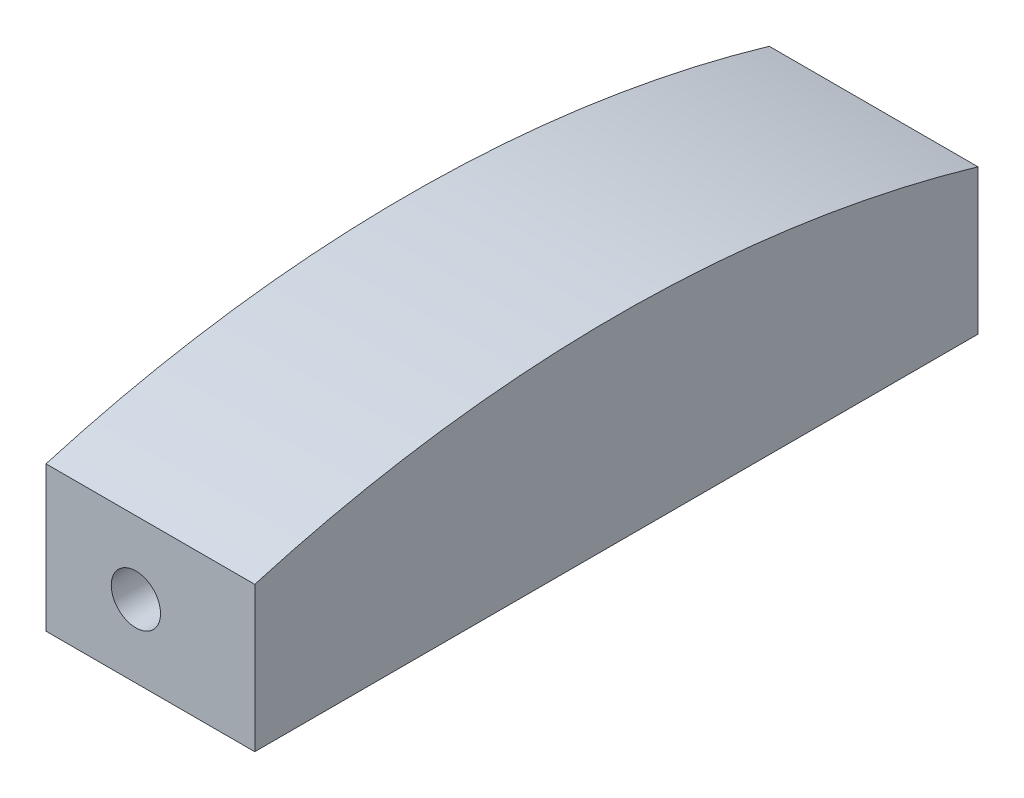
SolidWorks part; units mm, degrees
ref_plane "Front Plane" through (0, 0, 0) normal (0, 0, 1) x (1, 0, 0)
ref_plane "Top Plane" through (0, 0, 0) normal (0, 1, 0) x (1, 0, 0)
ref_plane "Right Plane" through (0, 0, 0) normal (1, 0, 0) x (0, 0, -1)
sketch "Sketch1" plane through (0, 0, 0) normal (0, 1, 0) x (1, 0, 0)
  line L1 (0, 0) -> (18.288, 0)
  line L2 (0, 0) -> (0, 63.357)
  line L3 (0, 63.357) -> (18.288, 63.357)
  line L4 (18.288, 0) -> (18.288, 63.357)
  line L5 (2.794, 58.277) -> (12.954, 58.277)
  line L6 (2.794, 58.277) -> (2.794, 53.197)
  line L7 (2.794, 53.197) -> (12.954, 53.197)
  line L8 (12.954, 58.277) -> (12.954, 53.197)
  line L9 (2.794, 10.16) -> (12.954, 10.16)
  line L10 (2.794, 10.16) -> (2.794, 5.08)
  line L11 (2.794, 5.08) -> (12.954, 5.08)
  line L12 (12.954, 10.16) -> (12.954, 5.08)
  dimension "D1" = 18.288
  dimension "D2" = 5.08
  dimension "D3" = 10.16
  dimension "D4" = 5.08
  dimension "D5" = 5.08
  dimension "D6" = 2.794
  dimension "D7" = 5.08
  dimension "D9" = 43.037
extrude "Boss-Extrude1" add sketch "Sketch1" along normal blind 12.7
sketch "Sketch2" plane through (18.288, 0, 0) normal (1, 0, 0) x (0, 0, -1)
  line L0 (0, 12.7) -> (63.357, 12.7)
  arc A0 (0, 12.7) -> (63.357, 12.7) centre (31.6785, -95.6141) cw
extrude "Boss-Extrude2" add sketch "Sketch2" against normal up to surface (18.288 mm away) up to face at (0, 6.35, -31.6785)
sketch "Sketch6" plane through (0, 0, 0) normal (0, 0, 1) x (1, 0, 0)
  line L0 (0, 0) -> (18.288, 0) construction
  line L1 (0, 12.7) -> (18.288, 12.7) construction
  circle A0 centre (7.874, 6.35) radius 2.159
  dimension "D3" = 4.318
  dimension "D1" = 12.7
  dimension "D2" = 6.35
extrude "Cut-Extrude1" cut sketch "Sketch6" against normal blind 3.81 and the other way through all
sketch "Sketch9" plane through (0, 0, -63.357) normal (0, 0, -1) x (-1, 0, 0)
  line L0 (-18.288, 0) -> (0, 0) construction
  line L1 (0, 12.7) -> (0, 0) construction
  circle A0 centre (-8.128, 6.35) radius 2.159
  dimension "D1" = 4.318
  dimension "D2" = 6.35
  dimension "D3" = 8.128
extrude "Cut-Extrude2" cut sketch "Sketch9" against normal blind 3.81 and the other way through all
sketch "Sketch10" plane through (0, 0, -53.197) normal (0, 0, -1) x (-1, 0, 0)
  circle A0 centre (-8.128, 6.35) radius 1.778
  dimension "D1" = 3.556
extrude "Cut-Extrude3" cut sketch "Sketch10" against normal through all both and the other way through all
